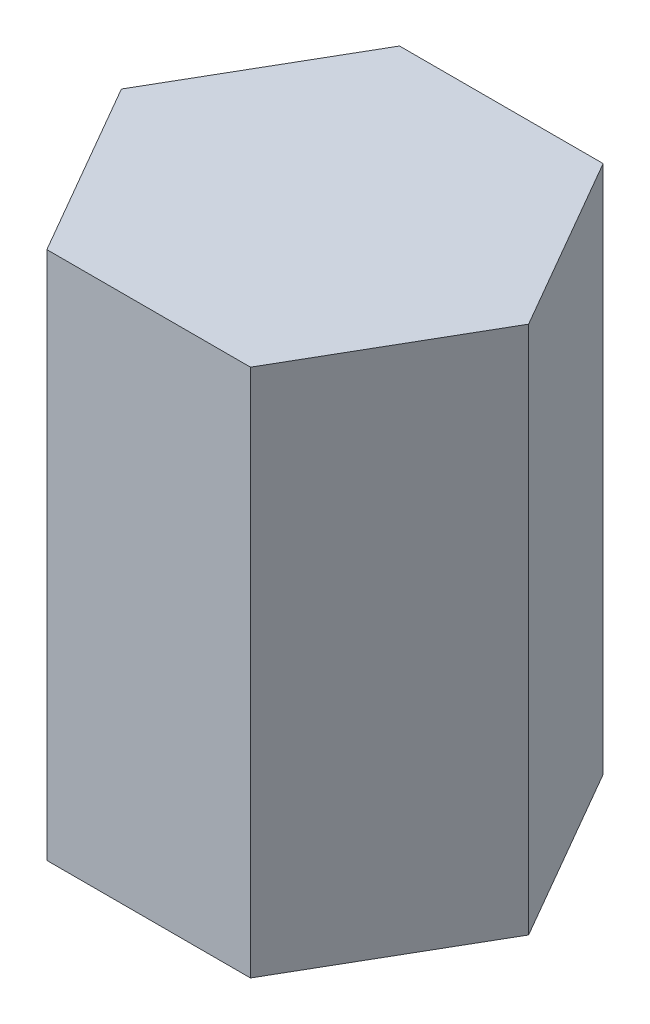
SolidWorks part; units mm, degrees
ref_plane "前视基准面" through (0, 0, 0) normal (0, 0, 1) x (1, 0, 0)
ref_plane "上视基准面" through (0, 0, 0) normal (0, 1, 0) x (1, 0, 0)
ref_plane "右视基准面" through (0, 0, 0) normal (1, 0, 0) x (0, 0, -1)
other "Configuration Table"
sketch "草图1" plane through (0, 0, 0) normal (0, 1, 0) x (1, 0, 0)
  line L1 (57.735, 0) -> (28.8675, 50)
  line L2 (28.8675, 50) -> (-28.8675, 50)
  line L3 (-28.8675, 50) -> (-57.735, 0)
  line L4 (-57.735, 0) -> (-28.8675, -50)
  line L5 (-28.8675, -50) -> (28.8675, -50)
  line L6 (28.8675, -50) -> (57.735, 0)
  circle A0 centre (0, 0) radius 50 construction
  dimension "D1" = 100
extrude "凸台-拉伸1" add sketch "草图1" along normal mid plane 150
